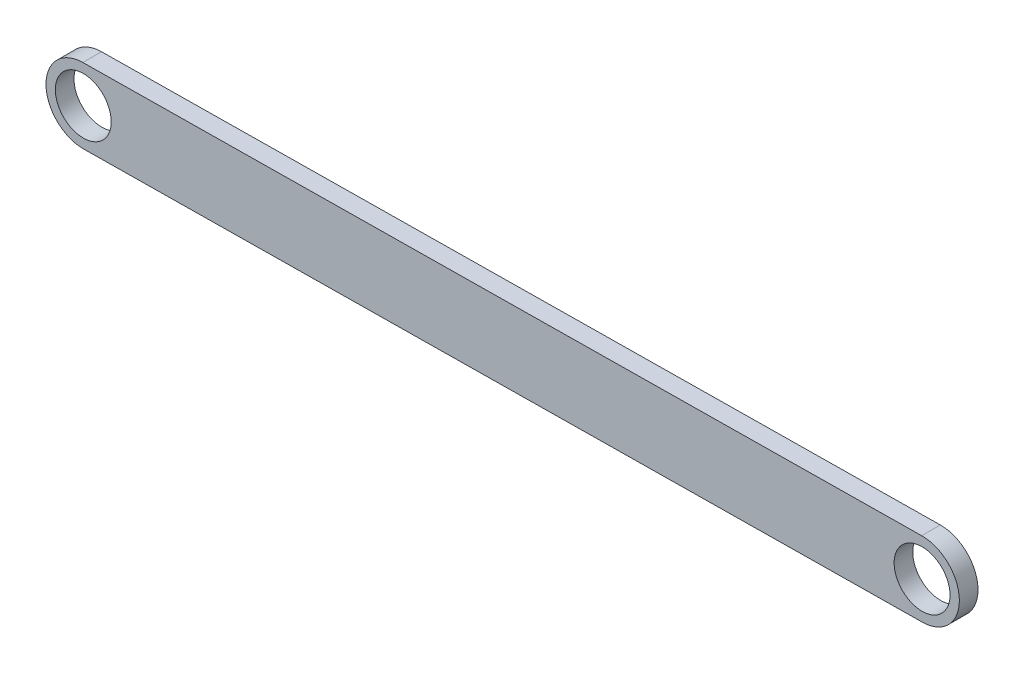
SolidWorks part; units mm, degrees
ref_plane "Спереди" through (0, 0, 0) normal (0, 0, 1) x (1, 0, 0)
ref_plane "Сверху" through (0, 0, 0) normal (0, 1, 0) x (1, 0, 0)
ref_plane "Справа" through (0, 0, 0) normal (1, 0, 0) x (0, 0, -1)
other "Configuration Table"
sketch "Эскиз1" plane through (0, 0, 0) normal (0, 0, 1) x (1, 0, 0)
  line L0 (0, 0) -> (450, 5.1411) construction
  line L1 (-0.2285, 20) -> (449.7715, 25.1411)
  line L2 (0.2285, -20) -> (450.2285, -14.8589)
  arc A0 (-0.2285, 20) -> (0.2285, -20) centre (0, 0) ccw
  arc A1 (450.2285, -14.8589) -> (449.7715, 25.1411) centre (450, 5.1411) ccw
  circle A2 centre (0, 0) radius 15
  circle A3 centre (450, 5.1411) radius 15
  point P3 (225, 2.5706)
  dimension "D3" = 30
  dimension "D4" = 30
  dimension "D1" = 450
  dimension "D2" = 40
extrude "Бобышка-Вытянуть1" add sketch "Эскиз1" along normal blind 10
